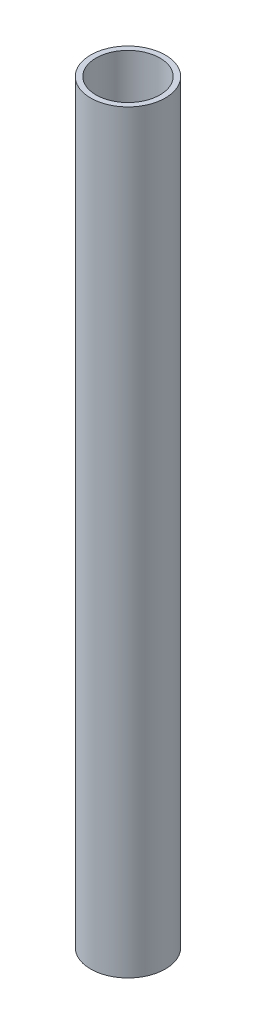
SolidWorks part; units mm, degrees
ref_plane "Alzado" through (0, 0, 0) normal (0, 0, 1) x (1, 0, 0)
ref_plane "Planta" through (0, 0, 0) normal (0, 1, 0) x (1, 0, 0)
ref_plane "Vista lateral" through (0, 0, 0) normal (1, 0, 0) x (0, 0, -1)
sketch "Croquis1" plane through (0, 0, 0) normal (0, 1, 0) x (1, 0, 0)
  circle A0 centre (0, 0) radius 14
  circle A1 centre (0, 0) radius 12
  dimension "D1" = 28
  dimension "D2" = 2
extrude "Saliente-Extruir1" add sketch "Croquis1" along normal blind 283
